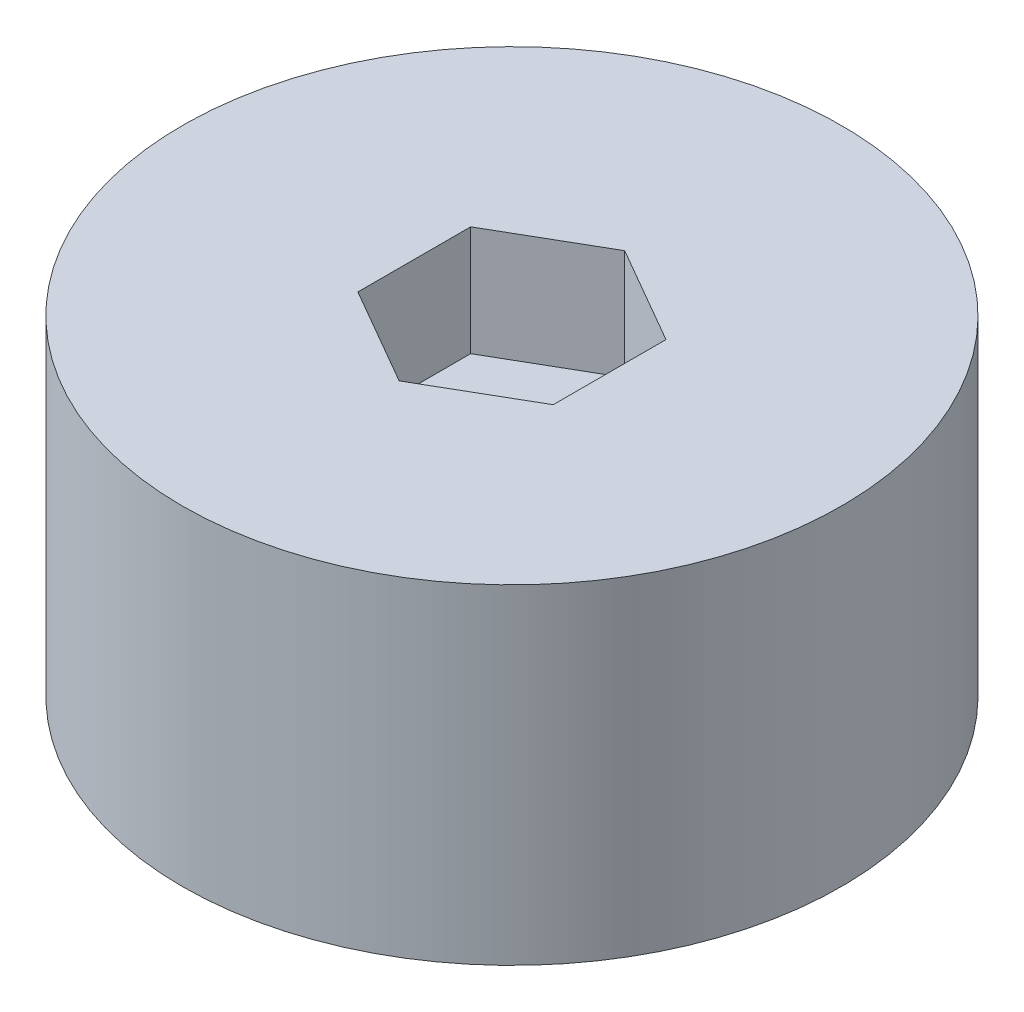
SolidWorks part; units mm, degrees
ref_plane "Front Plane" through (0, 0, 0) normal (0, 0, 1) x (1, 0, 0)
ref_plane "Top Plane" through (0, 0, 0) normal (0, 1, 0) x (1, 0, 0)
ref_plane "Right Plane" through (0, 0, 0) normal (1, 0, 0) x (0, 0, -1)
sketch "Sketch1" plane through (0, 0, 0) normal (0, 1, 0) x (1, 0, 0)
  circle A0 centre (0, 0) radius 15
  dimension "D1" = 30
extrude "Boss-Extrude1" add sketch "Sketch1" along normal blind 15 contours A0
sketch "Sketch2" plane through (0, 0, 0) normal (0, -1, 0) x (1, 0, 0)
  circle A0 centre (0, 0) radius 10.48
  dimension "D1" = 20.96
extrude "Cut-Extrude1" cut sketch "Sketch2" against normal blind 4
sketch "Sketch7" plane through (0, 15, 0) normal (0, 1, 0) x (1, 0, 0)
  line L0 (0, 5.1326) -> (-4.445, 2.5663)
  line L1 (-4.445, 2.5663) -> (-4.445, -2.5663)
  line L2 (-4.445, -2.5663) -> (0, -5.1326)
  line L3 (0, -5.1326) -> (4.445, -2.5663)
  line L4 (4.445, -2.5663) -> (4.445, 2.5663)
  line L5 (4.445, 2.5663) -> (0, 5.1326)
  line L6 (0, 15) -> (0, -15) construction
  line L7 (-15, 0) -> (15, 0) construction
  line L8 (0, 5.1326) -> (0, -5.1326) construction
  line L9 (-4.445, 0) -> (4.445, 0) construction
  line L10 (4.445, 2.5663) -> (-4.445, -2.5663) construction
  line L11 (-4.445, 2.5663) -> (4.445, -2.5663) construction
  circle A0 centre (0, 0) radius 15 construction
  point P15 (0, 0)
  point P17 (0, 0)
extrude "Cut-Extrude2" cut sketch "Sketch7" against normal blind 5
